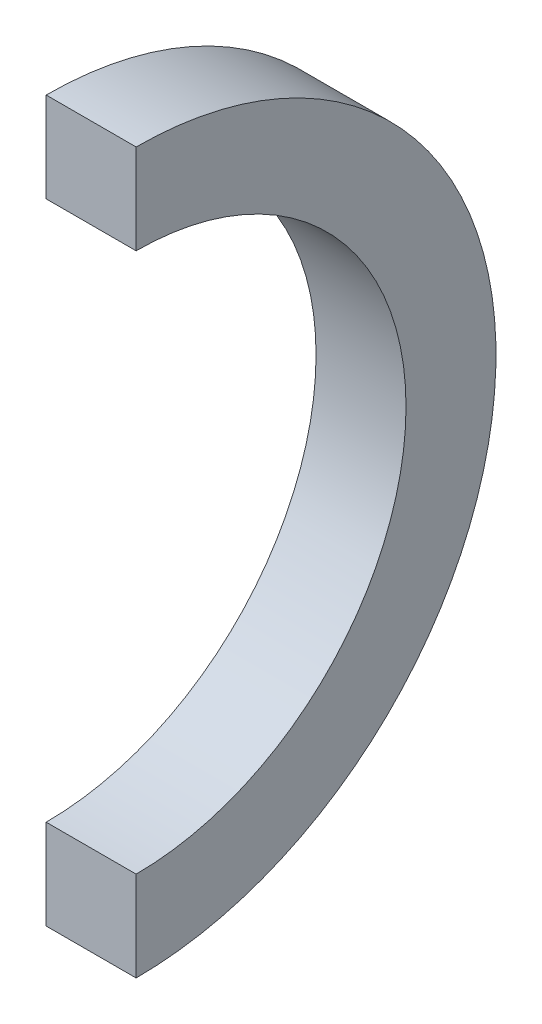
SolidWorks part; units mm, degrees
ref_plane "Front Plane" through (0, 0, 0) normal (0, 0, 1) x (1, 0, 0)
ref_plane "Top Plane" through (0, 0, 0) normal (0, 1, 0) x (1, 0, 0)
ref_plane "Right Plane" through (0, 0, 0) normal (1, 0, 0) x (0, 0, -1)
sketch "Sketch1" plane through (0, 0, 0) normal (0, 0, 1) x (1, 0, 0)
  line L1 (0, 0) -> (-25.4, 0)
  line L2 (0, 0) -> (0, 25.4)
  line L3 (0, 25.4) -> (-25.4, 25.4)
  line L4 (-25.4, 0) -> (-25.4, 25.4)
  dimension "D1" = 25.4
  dimension "D2" = 25.4
sketch "Sketch2" plane through (0, 0, 0) normal (0, 0, 1) x (1, 0, 0)
  line L0 (-25.4, 101.6) -> (0, 101.6)
  line L1 (0, 25.4) -> (-25.4, 25.4) construction
  dimension "D1" = 25.4
  dimension "D2" = 76.2
revolve "Revolve1" add sketch "Sketch1" angle 180 about L0
